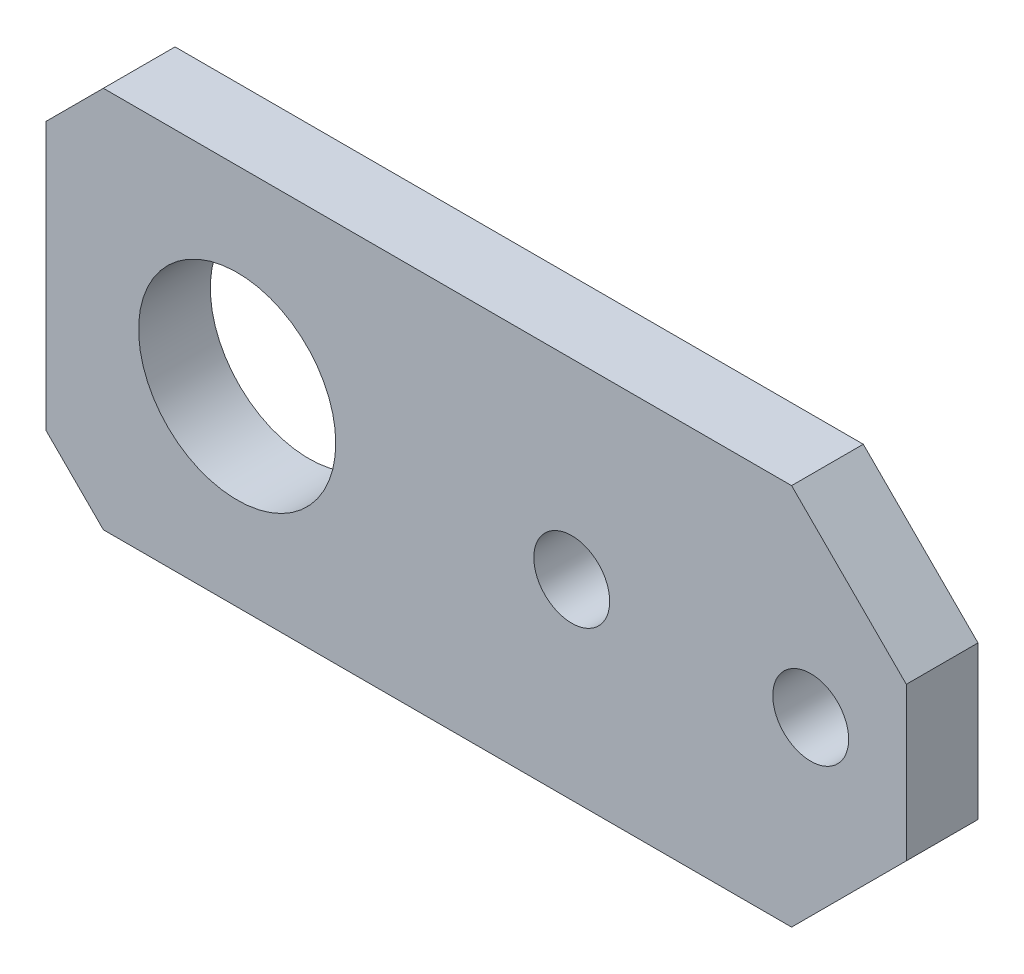
SolidWorks part; units mm, degrees
material "Plain Carbon Steel"
ref_plane "Front" through (0, 0, 0) normal (0, 0, 1) x (1, 0, 0)
ref_plane "Top" through (0, 0, 0) normal (0, 1, 0) x (1, 0, 0)
ref_plane "Right" through (0, 0, 0) normal (1, 0, 0) x (0, 0, -1)
sketch "Sketch1" plane through (0, 0, 0) normal (0, 0, 1) x (1, 0, 0)
  line L1 (-57.15, -25.4) -> (57.15, -25.4)
  line L2 (-57.15, -25.4) -> (-57.15, 25.4)
  line L3 (-57.15, 25.4) -> (57.15, 25.4)
  line L4 (57.15, -25.4) -> (57.15, 25.4)
  line L5 (-57.15, -25.4) -> (57.15, 25.4) construction
  line L6 (-57.15, 25.4) -> (57.15, -25.4) construction
  point P0 (0, 0)
  dimension "D1" = 114.3
  dimension "D2" = 50.8
extrude "Boss-Extrude1" add sketch "Sketch1" along normal blind 9.525
sketch "Sketch2" plane through (0, 0, 9.525) normal (0, 0, 1) x (1, 0, 0)
  line L0 (-57.15, 0) -> (-31.75, 0) construction
  line L1 (-57.15, 25.4) -> (-57.15, -25.4) construction
  line L2 (-31.75, 0) -> (12.7, 0) construction
  line L3 (12.7, 0) -> (44.45, 0) construction
  line L4 (44.45, 0) -> (57.15, 0) construction
  line L5 (57.15, -25.4) -> (57.15, 25.4) construction
  dimension "D1" = 12.7
  dimension "D2" = 31.75
  dimension "D3" = 25.4
hole_wizard "3/8 Clearance Hole1" positions "Sketch4" profile "Sketch3" hole size "3/8" standard "ANSI Inch" end condition through all
sketch "Sketch4" plane through (0, 0, 9.525) normal (0, 0, 1) x (1, 0, 0)
  point P0 (44.45, 0)
  point P3 (12.7, 0)
sketch "Sketch3" plane through (44.45, 0, 9.525) normal (1, 0, 0) x (0, -1, 0)
  line L0 (0, 0) -> (0, 9.525)
  line L1 (0, 9.525) -> (5.0419, 9.525)
  line L2 (5.0419, 9.525) -> (5.0419, 0)
  line L5 (5.0419, 0) -> (0, 0)
  line L11 (0, -6.35) -> (0, 107.95) construction
  dimension "Thru Hole Dia." = 10.0838
  dimension "Thru Hole Depth" = 9.525
hole_wizard "1 Clearance Hole1" positions "Sketch6" profile "Sketch5" hole size "1" standard "ANSI Inch" end condition through all
sketch "Sketch6" plane through (0, 0, 9.525) normal (0, 0, 1) x (1, 0, 0)
  point P0 (-31.75, 0)
sketch "Sketch5" plane through (-31.75, 0, 9.525) normal (1, 0, 0) x (0, -1, 0)
  line L0 (0, 0) -> (0, 9.525)
  line L1 (0, 9.525) -> (13.0962, 9.525)
  line L2 (13.0962, 9.525) -> (13.0962, 0)
  line L5 (13.0962, 0) -> (0, 0)
  line L11 (0, -6.35) -> (0, 107.95) construction
  dimension "Thru Hole Dia." = 26.1925
  dimension "Thru Hole Depth" = 9.525
chamfer "Chamfer1" distance 7.62 angle 45 2 edges at (-57.15, -25.4, 4.7625) (-57.15, 25.4, 4.7625)
chamfer "Chamfer2" distance 15.24 angle 45 2 edges at (57.15, 25.4, 4.7625) (57.15, -25.4, 4.7625)
